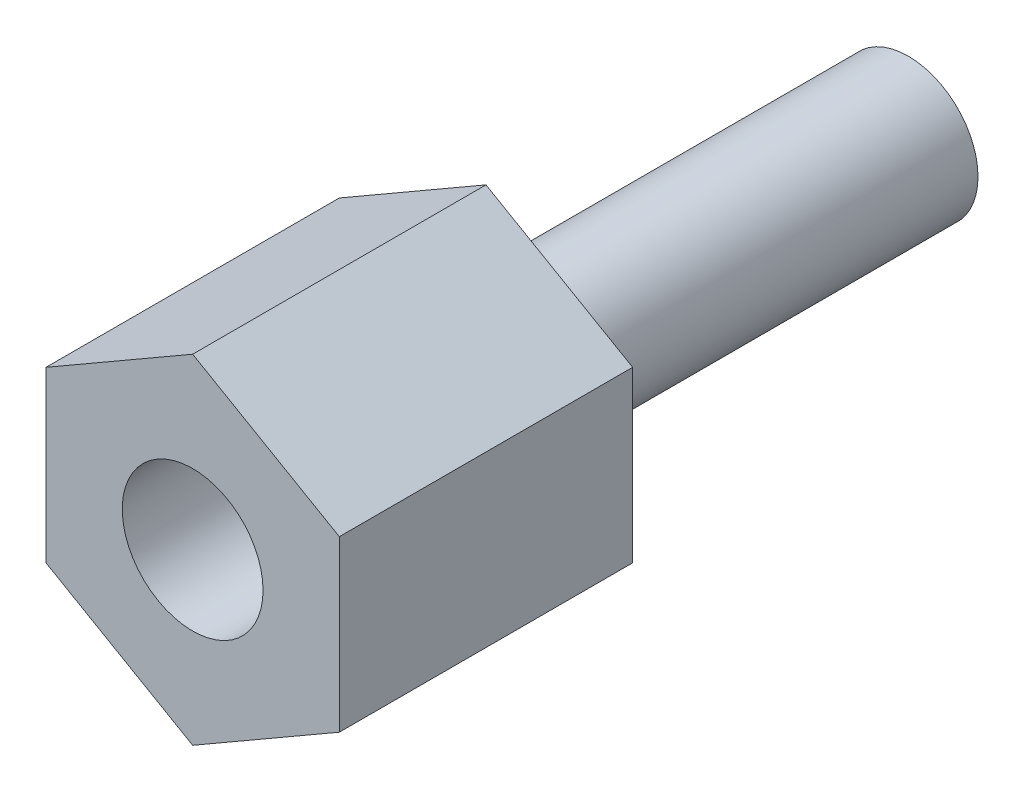
SolidWorks part; units mm, degrees
ref_plane "Front Plane" through (0, 0, 0) normal (0, 0, 1) x (1, 0, 0)
ref_plane "Top Plane" through (0, 0, 0) normal (0, 1, 0) x (1, 0, 0)
ref_plane "Right Plane" through (0, 0, 0) normal (1, 0, 0) x (0, 0, -1)
sketch "Sketch1" plane through (0, 0, 0) normal (0, 0, 1) x (1, 0, 0)
  line L1 (0, 2.7496) -> (-2.3812, 1.3748)
  line L2 (-2.3812, 1.3748) -> (-2.3812, -1.3748)
  line L3 (-2.3812, -1.3748) -> (0, -2.7496)
  line L4 (0, -2.7496) -> (2.3813, -1.3748)
  line L5 (2.3813, -1.3748) -> (2.3812, 1.3748)
  line L6 (2.3812, 1.3748) -> (0, 2.7496)
  circle A0 centre (0, 0) radius 2.3812 construction
  dimension "D1" = 4.7625
extrude "Boss-Extrude1" add sketch "Sketch1" along normal blind 4.7625
sketch "Sketch2" plane through (0, 0, 0) normal (0, 0, -1) x (-1, 0, 0)
  circle A0 centre (0, 0) radius 1.1303
  dimension "D1" = 2.2606
extrude "Boss-Extrude2" add sketch "Sketch2" along normal blind 6.858
sketch "Sketch3" plane through (0, 0, 4.7625) normal (0, 0, 1) x (1, 0, 0)
  circle A0 centre (0, 0) radius 1.143
  dimension "D1" = 2.286
extrude "Cut-Extrude1" cut sketch "Sketch3" against normal blind 2.54
